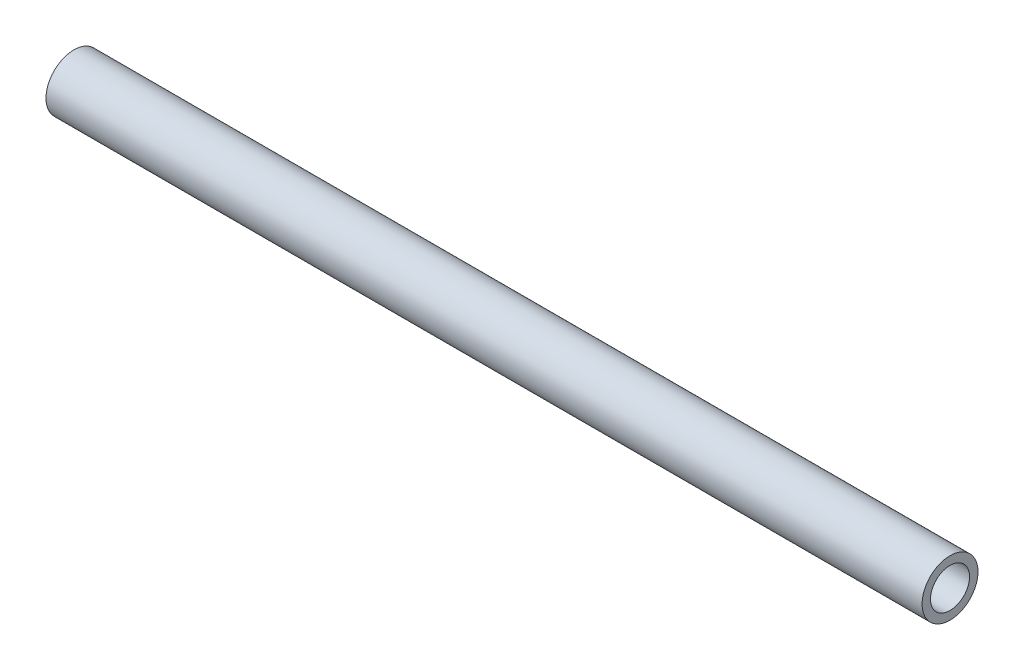
SolidWorks part; units mm, degrees
ref_plane "Front Plane" through (0, 0, 0) normal (0, 0, 1) x (1, 0, 0)
ref_plane "Top Plane" through (0, 0, 0) normal (0, 1, 0) x (1, 0, 0)
ref_plane "Right Plane" through (0, 0, 0) normal (1, 0, 0) x (0, 0, -1)
sketch "Sketch2" plane through (0, 0, 0) normal (1, 0, 0) x (0, 0, -1)
  circle A0 centre (0, 0) radius 7.366
  circle A1 centre (0, 0) radius 10.541
  dimension "D1" = 21.082
  dimension "D2" = 3.175
extrude "Boss-Extrude1" add sketch "Sketch2" along normal blind 330.2
